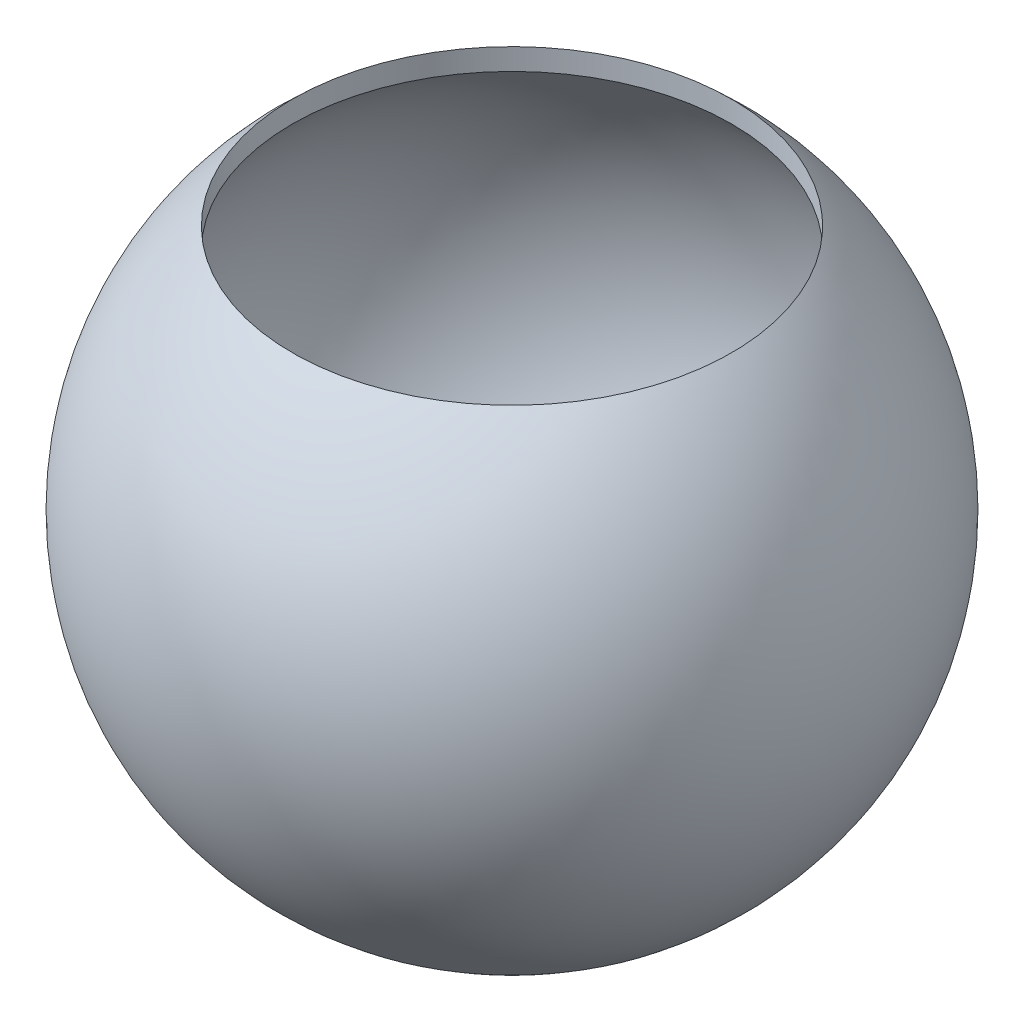
SolidWorks part; units mm, degrees
ref_plane "前视基准面" through (0, 0, 0) normal (0, 0, 1) x (1, 0, 0)
ref_plane "上视基准面" through (0, 0, 0) normal (0, 1, 0) x (1, 0, 0)
ref_plane "右视基准面" through (0, 0, 0) normal (1, 0, 0) x (0, 0, -1)
sketch "草图1" plane through (0, 0, 0) normal (0, 0, 1) x (1, 0, 0)
  line L1 (0, -10.5) -> (0, -10)
  line L2 (0, 10) -> (0, 10.5)
  arc A0 (0, -10) -> (0, 10) centre (0, 0) ccw
  arc A1 (0, -10.5) -> (0, 10.5) centre (0, 0) ccw
  point P6 (0, 0)
  point P9 (0, 0)
  dimension "D1" = 20
  dimension "D2" = 21
revolve "旋转1" add sketch "草图1" angle 360 about L2
ref_plane "基准面1" through (0, 10.5, 0) normal (0, 1, 0) x (1, 0, 0)
sketch "草图2" plane through (0, 10.5, 0) normal (0, 1, 0) x (1, 0, 0)
  circle A0 centre (0, 0) radius 7
  dimension "D1" = 14
extrude "切除-拉伸1" cut sketch "草图2" against normal blind 10
ref_plane "基准面4" through (0, -9.934, 0) normal (0, 1, 0) x (1, 0, 0)
sketch "草图5" plane through (0, -9.934, 0) normal (0, 1, 0) x (1, 0, 0)
  circle A0 centre (0, 0) radius 2.5
  dimension "D1" = 5
extrude "切除-拉伸3" cut sketch "草图5" along normal blind 10
sketch "草图6" plane through (0, -9.934, 0) normal (0, 1, 0) x (1, 0, 0)
  circle A0 centre (0, 0) radius 2.5
  dimension "D1" = 5
extrude "切除-拉伸4" cut sketch "草图6" against normal blind 10
